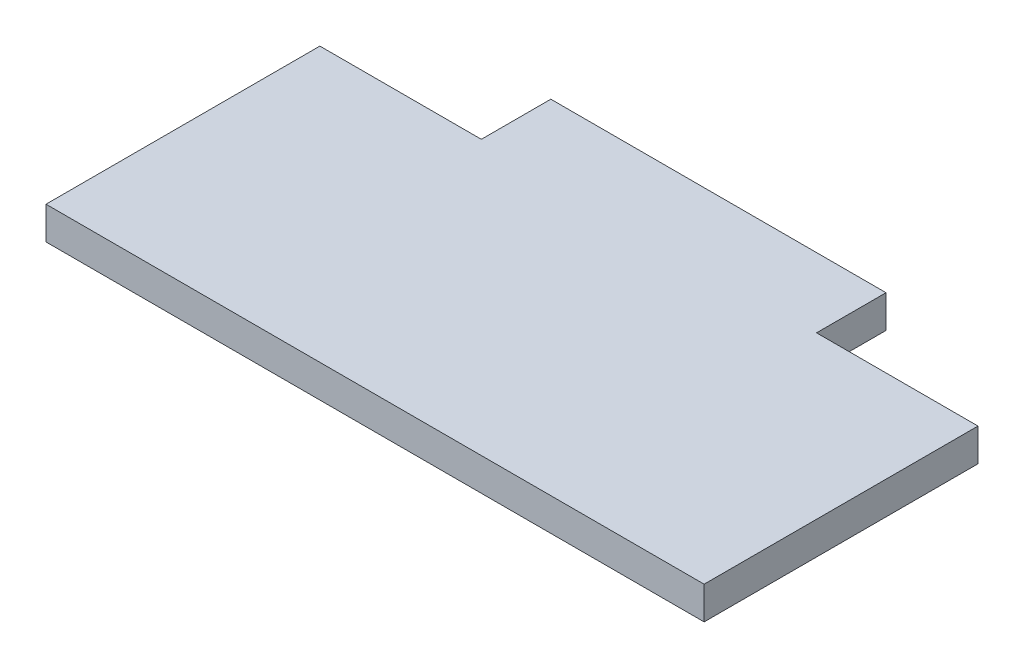
SolidWorks part; units mm, degrees
ref_plane "Front Plane" through (0, 0, 0) normal (0, 0, 1) x (1, 0, 0)
ref_plane "Top Plane" through (0, 0, 0) normal (0, 1, 0) x (1, 0, 0)
ref_plane "Right Plane" through (0, 0, 0) normal (1, 0, 0) x (0, 0, -1)
sketch "Sketch1" plane through (0, 0, 0) normal (0, 1, 0) x (1, 0, 0)
  line L0 (-65.0875, 0) -> (-65.0875, 26.9875)
  line L1 (-127.7937, 0) -> (-65.0875, 0)
  line L2 (-127.7937, 0) -> (-127.7937, -106.3625)
  line L3 (-127.7937, -106.3625) -> (127.7937, -106.3625)
  line L4 (127.7937, 0) -> (127.7937, -106.3625)
  line L5 (-65.0875, 26.9875) -> (65.0875, 26.9875)
  line L6 (65.0875, 26.9875) -> (65.0875, 0)
  line L7 (65.0875, 0) -> (127.7937, 0)
  dimension "D1" = 255.5875
  dimension "D2" = 106.3625
  dimension "D4" = 130.175
  dimension "D5" = 26.9875
extrude "Boss-Extrude1" add sketch "Sketch1" along normal blind 12.7
